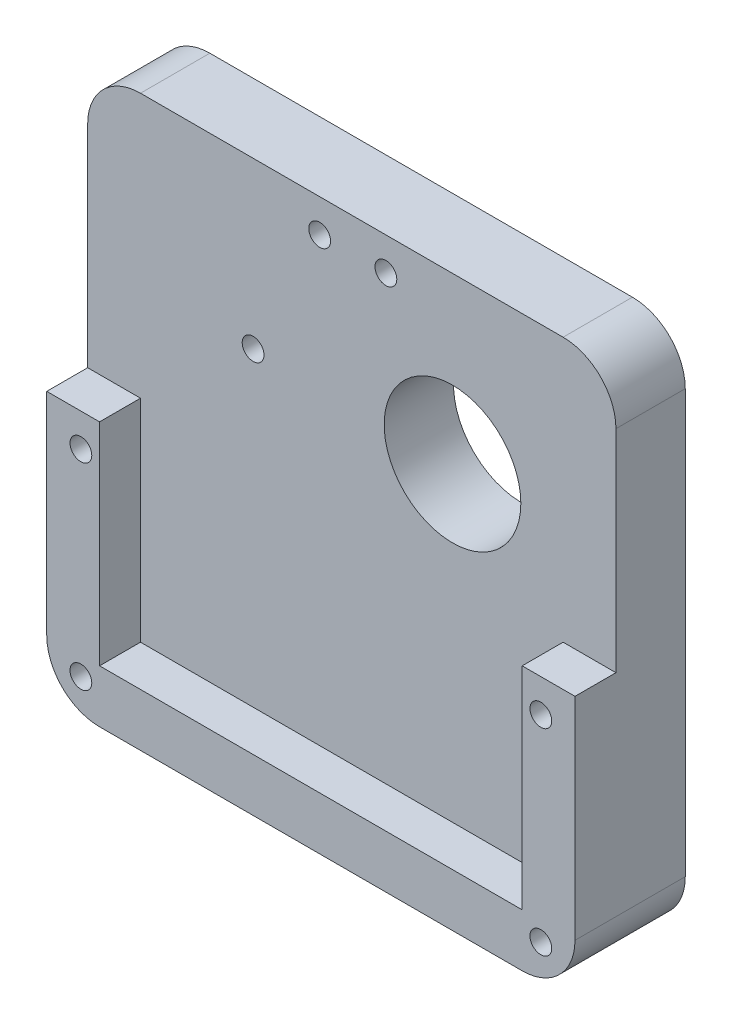
SolidWorks part; units mm, degrees
ref_plane "前视基准面" through (0, 0, 0) normal (0, 0, 1) x (1, 0, 0)
ref_plane "上视基准面" through (0, 0, 0) normal (0, 1, 0) x (1, 0, 0)
ref_plane "右视基准面" through (0, 0, 0) normal (1, 0, 0) x (0, 0, -1)
sketch "草图1" plane through (0, 0, 0) normal (0, 0, 1) x (1, 0, 0)
  line L1 (-45, 40) -> (35, 40)
  line L2 (-45, 40) -> (-45, -40)
  line L3 (-45, -40) -> (35, -40)
  line L4 (35, 40) -> (35, -40)
extrude "凸台-拉伸1" add sketch "草图1" along normal blind 10.5
sketch "草图3" plane through (0, 0, 10.5) normal (0, 0, 1) x (1, 0, 0)
  line L0 (10.25, 15) -> (-19.95, 15) construction
  line L1 (-16.0291, 15) -> (-16.0291, 35) construction
  line L2 (-16.0291, 35) -> (26.8141, 35) construction
  circle A4 centre (-19.95, 15) radius 1.65
  circle A5 centre (10.25, 15) radius 22.4 construction
  circle A6 centre (-19.95, 15) radius 22.4 construction
  circle A7 centre (-9.8624, 35) radius 1.65
  circle A8 centre (0.1624, 35) radius 1.65
  circle A14 centre (10.25, 15) radius 10.35
  point P0 (10.25, 15)
  point P8 (0.1624, 35)
  point P11 (-9.8624, 35)
extrude "切除-拉伸1" cut sketch "草图3" against normal through all
sketch "草图5" plane through (-45, 0, 0) normal (-1, 0, 0) x (0, 0, 1)
  line L0 (0, -11.3386) -> (10.5, -11.3386)
  line L1 (0, -44) -> (0, 44) construction
  line L2 (10.5, 40) -> (10.5, -40) construction
fillet "圆角3" radius 8 1 edges at (35, 40, 5.25)
fillet "圆角4" radius 8 1 edges at (-45, 40, 5.25)
sketch "草图8" plane through (0, 0, 10.5) normal (0, 0, 1) x (1, 0, 0)
  line L0 (-45, -6.185) -> (35, -6.185)
  line L1 (-45, 32) -> (-45, -40) construction
  line L2 (35, -40) -> (35, 32) construction
  line L3 (27, 40) -> (-37, 40) construction
  line L4 (-29.6831, 40) -> (-29.6831, -40)
  line L5 (-45, -40) -> (35, -40) construction
fillet "圆角5" radius 8 1 edges at (-45, -40, 5.25)
fillet "圆角6" radius 8 1 edges at (35, -40, 5.25)
sketch "草图11" plane through (0, 0, 10.5) normal (0, 0, 1) x (1, 0, 0)
  line L0 (-45, 0) -> (-37, 0)
  line L1 (-45, 32) -> (-45, -32) construction
  line L2 (-37, 0) -> (-37, -32)
  line L3 (-37, -32) -> (27, -32)
  line L4 (27, -32) -> (27, 0)
  line L5 (27, 0) -> (35, 0)
  line L6 (35, -32) -> (35, 32) construction
  line L7 (-45, 0) -> (-45, -32)
  line L8 (-37, -40) -> (27, -40) construction
  line L9 (-37, -40) -> (27, -40)
  line L10 (35, -32) -> (35, 0)
  arc A0 (-45, -32) -> (-37, -40) centre (-37, -32) ccw
  arc A1 (27, -40) -> (35, -32) centre (27, -32) ccw
  arc A2 (27, -40) -> (35, -32) centre (27, -32) ccw construction
  point P0 (-37, 0)
  point P1 (27, 0)
  point P2 (-37, -32)
  point P3 (27, -32)
extrude "凸台-拉伸2" add sketch "草图11" along normal blind 6.2
sketch "草图12" plane through (0, 0, 10.5) normal (0, 0, 1) x (1, 0, 0)
  line L0 (27, -32) -> (32.6569, -37.6569) construction
  line L1 (-37, -32) -> (-42.6569, -37.6569) construction
  line L2 (-39.8284, 0) -> (-39.8284, -5) construction
  line L3 (29.8284, 0) -> (29.8284, -5) construction
  arc A0 (27, -40) -> (35, -32) centre (27, -32) ccw construction
  circle A1 centre (29.8284, -34.8284) radius 1.65
  arc A2 (-45, -32) -> (-37, -40) centre (-37, -32) ccw construction
  circle A3 centre (-39.8284, -34.8284) radius 1.65
  circle A4 centre (-39.8284, -5) radius 1.65
  circle A5 centre (29.8284, -5) radius 1.65
  point P0 (27, -32)
  point P7 (29.8284, -34.8284)
  point P18 (-39.8284, 0)
  point P19 (29.8284, 0)
extrude "切除-拉伸2" cut sketch "草图12" against normal through all both and the other way through all
